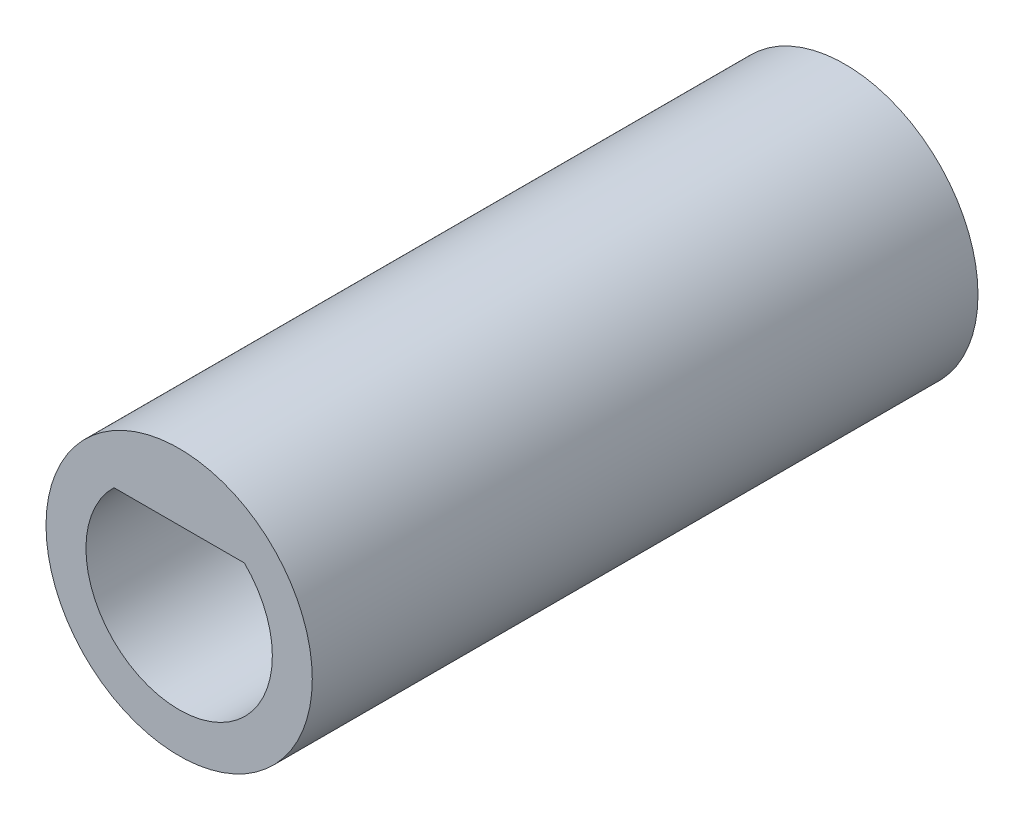
SolidWorks part; units mm, degrees
ref_plane "前视基准面" through (0, 0, 0) normal (0, 0, 1) x (1, 0, 0)
ref_plane "上视基准面" through (0, 0, 0) normal (0, 1, 0) x (1, 0, 0)
ref_plane "右视基准面" through (0, 0, 0) normal (1, 0, 0) x (0, 0, -1)
other "Configuration Table"
sketch "草图1" plane through (0, 0, 0) normal (0, 0, 1) x (1, 0, 0)
  circle A0 centre (0, 0) radius 3
  dimension "D1" = 6
extrude "凸台-拉伸1" add sketch "草图1" along normal blind 15
sketch "草图2" plane through (0, 0, 15) normal (0, 0, 1) x (1, 0, 0)
  line L0 (-1.4697, 1.5) -> (1.4697, 1.5)
  circle A0 centre (0, 0) radius 2.1
  dimension "D1" = 4.2
  dimension "D2" = 1.5
extrude "切除-拉伸1" cut sketch "草图2" against normal blind 6 contours L0 A0
sketch "草图3" plane through (0, 0, 0) normal (0, 0, -1) x (-1, 0, 0)
  line L1 (0.5, -2.25) -> (-0.5, -2.25)
  line L2 (0.5, -2.25) -> (0.5, 2.25)
  line L3 (0.5, 2.25) -> (-0.5, 2.25)
  line L4 (-0.5, -2.25) -> (-0.5, 2.25)
  line L5 (0.5, -2.25) -> (-0.5, 2.25) construction
  line L6 (0.5, 2.25) -> (-0.5, -2.25) construction
  line L7 (-2.25, -0.5) -> (2.25, -0.5)
  line L8 (-2.25, -0.5) -> (-2.25, 0.5)
  line L9 (-2.25, 0.5) -> (2.25, 0.5)
  line L10 (2.25, -0.5) -> (2.25, 0.5)
  line L11 (-2.25, -0.5) -> (2.25, 0.5) construction
  line L12 (-2.25, 0.5) -> (2.25, -0.5) construction
  point P0 (0, 0)
  point P6 (0, 0)
  dimension "D1" = 4.5
  dimension "D2" = 1
extrude "切除-拉伸2" cut sketch "草图3" against normal blind 8 contours L7 L4 L1 L2 | L7 L10 L9 L2 | L9 L4 L7 L2 | L9 L8 L7 L4 | L4 L9 L2 L3
fillet "圆角2" radius 0.2 36 edges at (0, 2.25, 0) (-1.375, 0.5, 0) (0, -2.25, 0) (2.25, 0, 0) (0.5, 2.25, 4) (0.5, 1.375, 0) (0.5, 0.5, 4) (2.25, 0.5, 4) (1.375, 0.5, 0) (-1.375, -0.5, 0) (-2.25, -0.5, 4) (-2.25, 0.5, 4) (-2.25, 0, 0) (-0.5, 0.5, 4) (-0.5, 2.25, 4) (-0.5, 1.375, 0) (-0.5, -2.25, 4) (-0.5, -0.5, 4) (-0.5, -1.375, 0) (2.25, -0.5, 4) (1.375, -0.5, 0) (0.5, -0.5, 4) (0.5, -2.25, 4) (0.5, -1.375, 0) (0, -2.25, 8) (0.5, -1.375, 8) (1.375, -0.5, 8) (2.25, 0, 8) (1.375, 0.5, 8) (0.5, 1.375, 8) (0, 2.25, 8) (-0.5, 1.375, 8) (-1.375, 0.5, 8) (-2.25, 0, 8) (-1.375, -0.5, 8) (-0.5, -1.375, 8)
